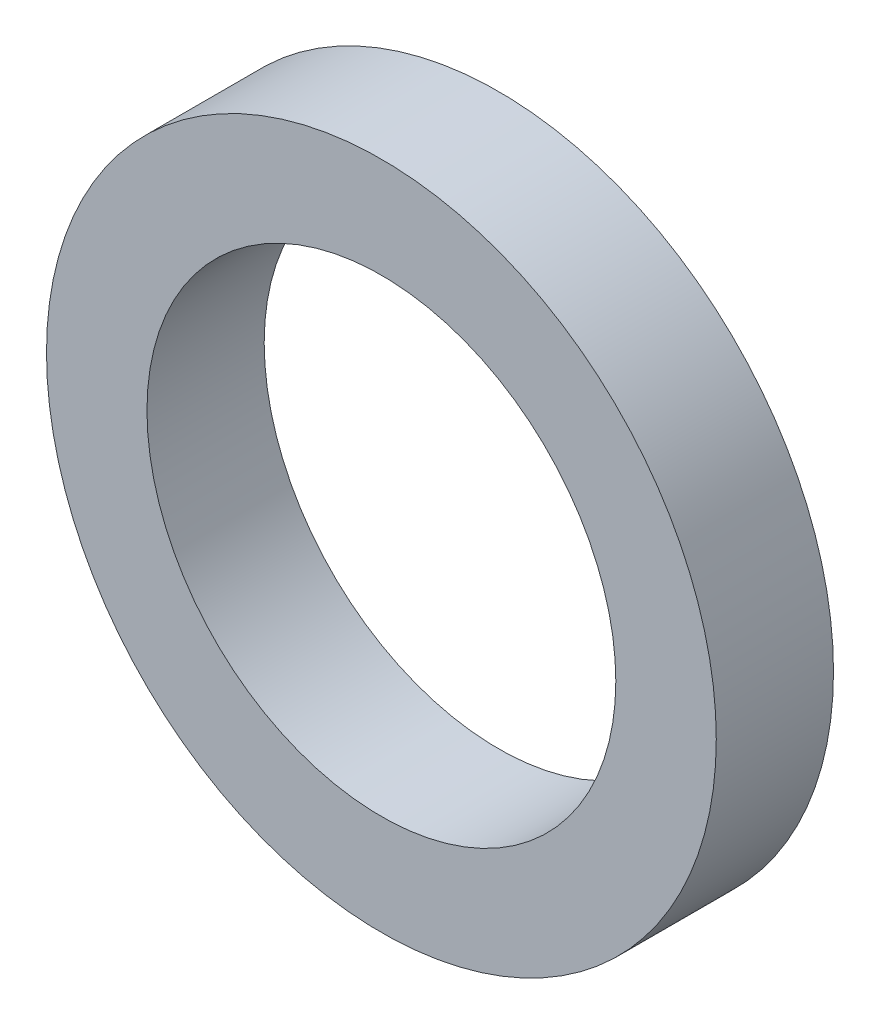
SolidWorks part; units mm, degrees
ref_plane "Front Plane" through (0, 0, 0) normal (0, 0, 1) x (1, 0, 0)
ref_plane "Top Plane" through (0, 0, 0) normal (0, 1, 0) x (1, 0, 0)
ref_plane "Right Plane" through (0, 0, 0) normal (1, 0, 0) x (0, 0, -1)
sketch "Sketch1" plane through (0, 0, 0) normal (0, 0, 1) x (1, 0, 0)
  circle A0 centre (0, 0) radius 20
  circle A1 centre (0, 0) radius 14
  dimension "D1" = 40
  dimension "D2" = 28
extrude "Boss-Extrude1" add sketch "Sketch1" along normal blind 7
